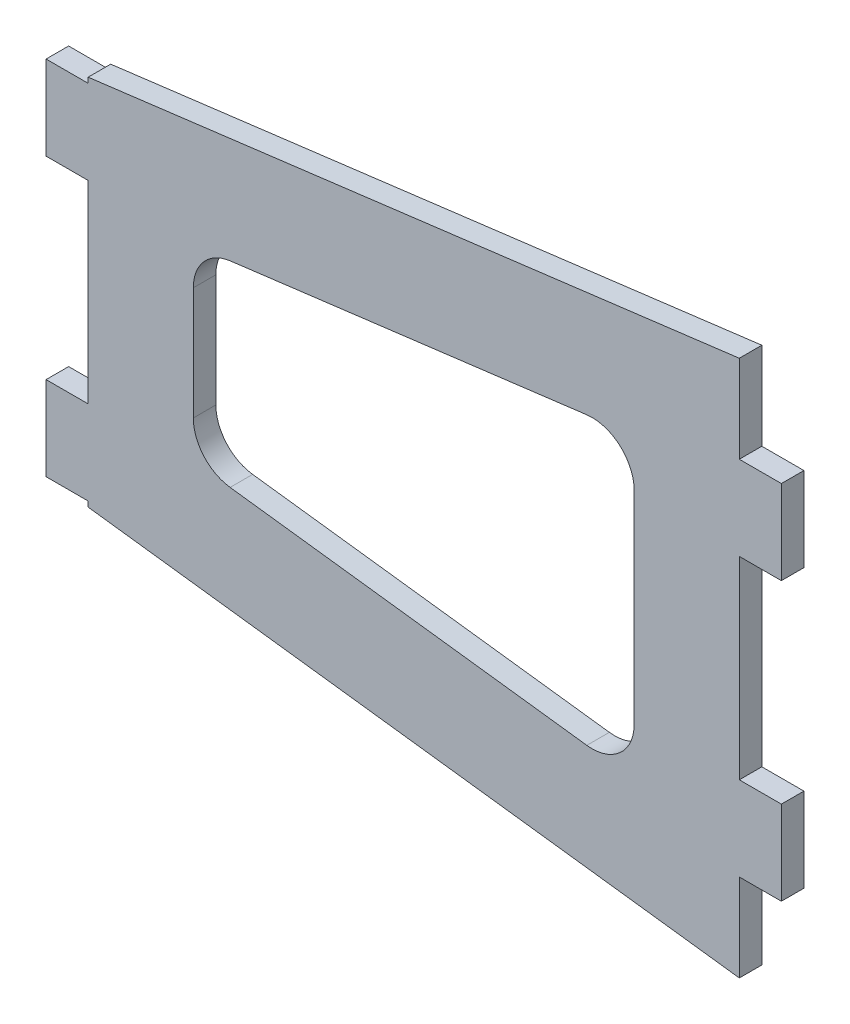
SolidWorks part; units mm, degrees
ref_plane "Front Plane" through (0, 0, 0) normal (0, 0, 1) x (1, 0, 0)
ref_plane "Top Plane" through (0, 0, 0) normal (0, 1, 0) x (1, 0, 0)
ref_plane "Right Plane" through (0, 0, 0) normal (1, 0, 0) x (0, 0, -1)
sketch "Sketch1" plane through (0, 0, 0) normal (0, 0, 1) x (1, 0, 0)
  line L0 (8672.1773, 2928.4418) -> (8678.5273, 2928.4418)
  line L1 (8567.5293, 2941.1418) -> (8573.8793, 2941.1418)
  line L2 (8672.1773, 2941.1418) -> (8678.5273, 2941.1418)
  line L3 (8672.1773, 2983.0518) -> (8678.5273, 2983.0518)
  line L4 (8567.5293, 2970.3518) -> (8573.8793, 2970.3518)
  line L5 (8672.1773, 2970.3518) -> (8678.5273, 2970.3518)
  line L6 (8573.8793, 2970.3518) -> (8573.8793, 2941.1418)
  line L7 (8589.7543, 2964.257) -> (8589.7543, 2947.2366)
  line L8 (8567.5293, 2983.0518) -> (8567.5293, 2970.3518)
  line L9 (8567.5293, 2941.1418) -> (8567.5293, 2928.4418)
  line L10 (8672.1773, 2970.3518) -> (8672.1773, 2941.1418)
  line L11 (8656.3023, 2971.0534) -> (8656.3023, 2940.4402)
  line L12 (8678.5273, 2983.0518) -> (8678.5273, 2970.3518)
  line L13 (8678.5273, 2941.1418) -> (8678.5273, 2928.4418)
  line L14 (8672.1773, 2915.2338) -> (8672.1773, 2928.4418)
  line L15 (8672.1773, 2996.2598) -> (8672.1773, 2983.0518)
  line L16 (8672.1773, 2996.2598) -> (8573.8793, 2983.8533)
  line L17 (8649.1571, 2977.3534) -> (8595.3091, 2970.5571)
  line L18 (8672.1773, 2915.2338) -> (8573.8793, 2927.6403)
  line L19 (8649.1571, 2934.1402) -> (8595.3091, 2940.9366)
  line L20 (8567.5293, 2983.0518) -> (8573.8793, 2983.0518)
  line L21 (8573.8793, 2983.0518) -> (8573.8793, 2983.8533)
  line L22 (8567.5293, 2928.4418) -> (8573.8793, 2928.4418)
  line L23 (8573.8793, 2928.4418) -> (8573.8793, 2927.6403)
  arc A0 (8589.7543, 2947.2366) -> (8595.3091, 2940.9366) centre (8596.1043, 2947.2366) ccw
  arc A1 (8649.1571, 2934.1402) -> (8656.3023, 2940.4402) centre (8649.9523, 2940.4402) ccw
  arc A2 (8595.3091, 2970.5571) -> (8589.7543, 2964.257) centre (8596.1043, 2964.257) ccw
  arc A3 (8656.3023, 2971.0534) -> (8649.1571, 2977.3534) centre (8649.9523, 2971.0534) ccw
extrude "Boss-Extrude1" add sketch "Sketch1" along normal blind 3.4036
